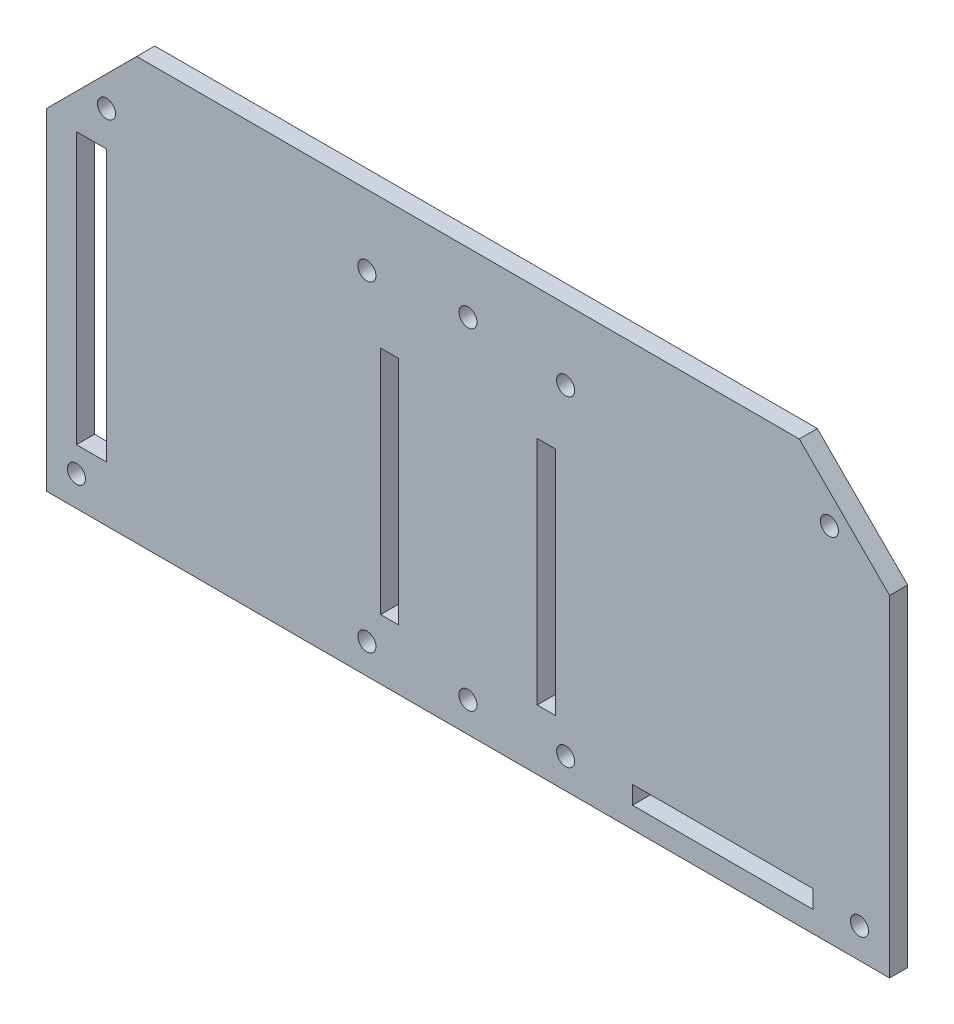
SolidWorks part; units mm, degrees
ref_plane "Alzado" through (0, 0, 0) normal (0, 0, 1) x (1, 0, 0)
ref_plane "Planta" through (0, 0, 0) normal (0, 1, 0) x (1, 0, 0)
ref_plane "Vista lateral" through (0, 0, 0) normal (1, 0, 0) x (0, 0, -1)
sketch "Croquis2" plane through (0, 0, 0) normal (0, 0, 1) x (1, 0, 0)
  line L1 (-70, -35) -> (70, -35)
  line L2 (-70, -35) -> (-70, 35)
  line L3 (-70, 35) -> (70, 35)
  line L4 (70, -35) -> (70, 35)
  line L5 (-70, -35) -> (70, 35) construction
  line L6 (-70, 35) -> (70, -35) construction
  point P0 (0, 0)
  dimension "D1" = 140
  dimension "D2" = 70
extrude "Saliente-Extruir1" add sketch "Croquis2" along normal blind 3
sketch "Croquis3" plane through (0, 0, 3) normal (0, 0, 1) x (1, 0, 0)
  line L0 (-70, 35) -> (-70, -35) construction
  line L1 (-70, -35) -> (70, -35) construction
  line L2 (70, -35) -> (70, 35) construction
  line L3 (70, 35) -> (-70, 35) construction
  circle A0 centre (-65, -30) radius 1.5
  circle A1 centre (65, -30) radius 1.5
  circle A2 centre (0, -30) radius 1.5
  circle A3 centre (-60, 25) radius 1.5
  circle A4 centre (60, 25) radius 1.5
  circle A5 centre (0, 25) radius 1.5
  dimension "D3" = 3
  dimension "D6" = 3
  dimension "D8" = 3
  dimension "D11" = 3
  dimension "D14" = 3
  dimension "D15" = 3
  dimension "D1" = 5
  dimension "D2" = 5
  dimension "D4" = 5
  dimension "D5" = 5
  dimension "D7" = 5
  dimension "D9" = 10
  dimension "D10" = 10
  dimension "D12" = 10
  dimension "D13" = 10
  dimension "D16" = 55
extrude "Cortar-Extruir1" cut sketch "Croquis3" against normal blind 3
chamfer "Chaflán2" distance 15 angle 45 2 edges at (-70, 35, 1.5) (70, 35, 1.5)
sketch "Croquis4" plane through (0, 0, 3) normal (0, 0, 1) x (1, 0, 0)
  line L0 (0, -41.8886) -> (0, 42.8843) construction
  line L1 (11.5, -25) -> (14.5, -25)
  line L2 (14.5, -25) -> (14.5, 13.3263)
  line L3 (-70, -35) -> (70, -35) construction
  line L4 (11.5, -25) -> (11.5, 13.3263)
  line L5 (11.5, 13.3263) -> (14.5, 13.3263)
  line L6 (-11.5, -25) -> (-14.5, -25)
  line L7 (-14.5, -25) -> (-14.5, 13.3263)
  line L8 (-14.5, 13.3263) -> (-11.5, 13.3263)
  line L9 (-11.5, 13.3263) -> (-11.5, -25)
  line L14 (27.3094, -28.5) -> (27.3094, -31.5)
  line L15 (-65, 19.1799) -> (-65, -25.8201)
  line L16 (-65, -25.8201) -> (-60, -25.8201)
  line L17 (-60, -25.8201) -> (-60, 19.1799)
  line L18 (-60, 19.1799) -> (-65, 19.1799)
  line L19 (-70, 20) -> (-70, -35) construction
  line L25 (27.3094, -31.5) -> (57.3094, -31.5)
  line L26 (57.3094, -31.5) -> (57.3094, -28.5)
  line L27 (57.3094, -28.5) -> (27.3094, -28.5)
  circle A0 centre (-16.7839, 23.3263) radius 1.5
  circle A1 centre (16.2161, 23.3263) radius 1.5
  circle A2 centre (-16.7839, -30) radius 1.5
  circle A3 centre (16.2161, -30) radius 1.5
  dimension "D2" = 10
  dimension "D7" = 3
  dimension "D8" = 3
  dimension "D10" = 3
  dimension "D11" = 3
  dimension "D1" = 14.5
  dimension "D3" = 14.5
  dimension "D4" = 3
  dimension "D5" = 3
  dimension "D6" = 33
  dimension "D9" = 10
  dimension "D12" = 5
  dimension "D13" = 5
  dimension "D14" = 33
  dimension "D15" = 5
  dimension "D16" = 5
  dimension "D17" = 45
  dimension "D18" = 30
extrude "Cortar-Extruir2" cut sketch "Croquis4" against normal blind 3
